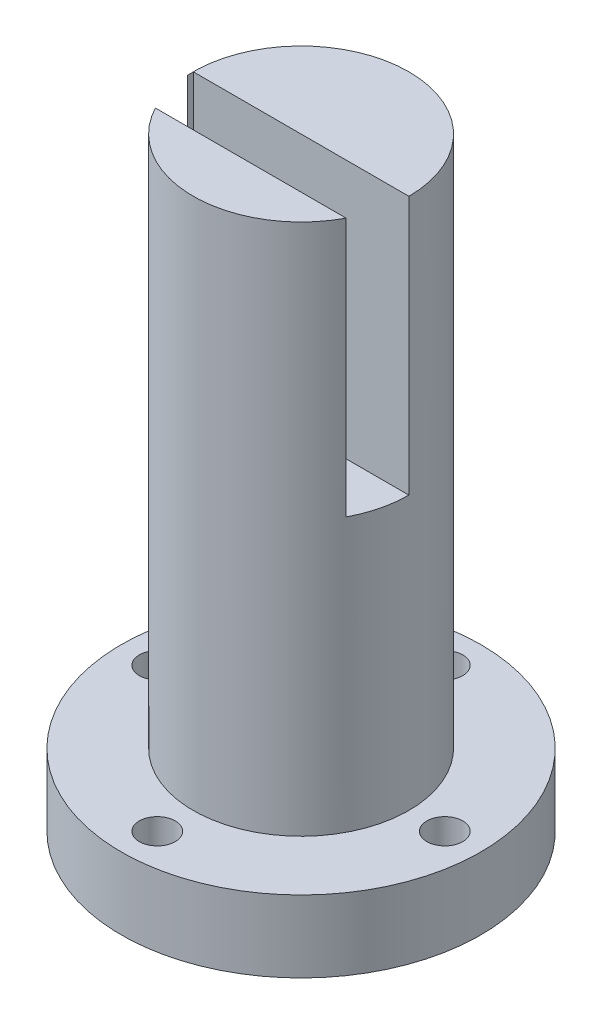
SolidWorks part; units mm, degrees
ref_plane "Front Plane" through (0, 0, 0) normal (0, 0, 1) x (1, 0, 0)
ref_plane "Top Plane" through (0, 0, 0) normal (0, 1, 0) x (1, 0, 0)
ref_plane "Right Plane" through (0, 0, 0) normal (1, 0, 0) x (0, 0, -1)
sketch "Sketch1" plane through (0, 0, 0) normal (0, 1, 0) x (1, 0, 0)
  circle A0 centre (0, 0) radius 15
  dimension "D1" = 30
extrude "Boss-Extrude1" add sketch "Sketch1" along normal blind 44 contours A0
sketch "Sketch2" plane through (0, 44, 0) normal (0, 1, 0) x (1, 0, 0)
  line L0 (15, 0) -> (15, -7)
  line L1 (15, 0) -> (-14.9788, 0)
  line L2 (15, -7) -> (-14.9788, -7)
  line L3 (-14.9788, 0) -> (-14.9788, -7)
  circle A0 centre (0, 0) radius 15 construction
  dimension "D1" = 7
extrude "Cut-Extrude1" cut sketch "Sketch2" against normal blind 36
sketch "Sketch4" plane through (0, 0, 0) normal (0, -1, 0) x (1, 0, 0)
  circle A0 centre (0, 0) radius 15
extrude "Boss-Extrude2" add sketch "Sketch4" along normal blind 30
sketch "Sketch5" plane through (0, -30, 0) normal (0, -1, 0) x (1, 0, 0)
  circle A0 centre (0, 0) radius 25
  dimension "D1" = 50
extrude "Boss-Extrude3" add sketch "Sketch5" along normal blind 10
sketch "Sketch6" plane through (0, -40, 0) normal (0, -1, 0) x (1, 0, 0)
  line L0 (0, 0) -> (0, 25)
  circle A0 centre (0, 0) radius 15
  circle A1 centre (0, 0) radius 25 construction
  circle A2 centre (0, 20) radius 2.5
  circle A3 centre (20, 0) radius 2.5
  circle A4 centre (0, -20) radius 2.5
  circle A5 centre (-20, 0) radius 2.5
  point P17 (0, 0)
  dimension "D1" = 30
  dimension "D2" = 5
  dimension "D3" = 20
  dimension "D4" = 4
extrude "Cut-Extrude2" cut sketch "Sketch6" against normal through all contours L0 A2 | L0 A2 | A3 | A4 | A5
